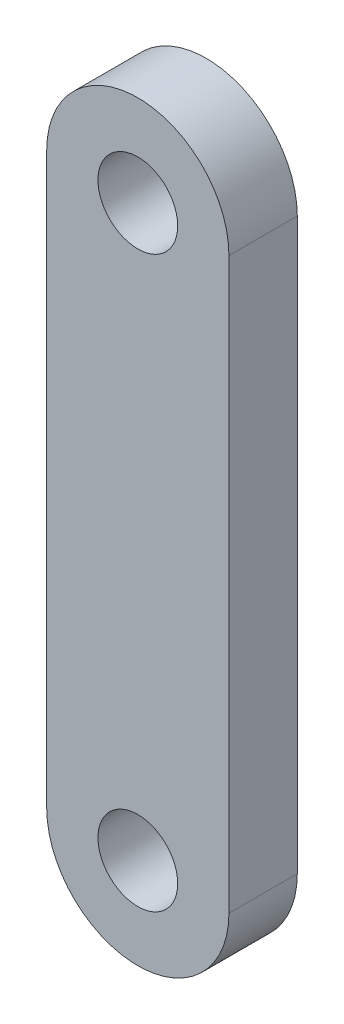
SolidWorks part; units mm, degrees
ref_plane "Plano frontal" through (0, 0, 0) normal (0, 0, 1) x (1, 0, 0)
ref_plane "Plano superior" through (0, 0, 0) normal (0, 1, 0) x (1, 0, 0)
ref_plane "Plano direito" through (0, 0, 0) normal (1, 0, 0) x (0, 0, -1)
sketch "Esboço1" plane through (0, 0, 0) normal (0, 0, 1) x (1, 0, 0)
  line L0 (0, 12.5) -> (0, -12.5) construction
  line L1 (0, 12.5) -> (0, -12.5) construction
  line L2 (4, 12.5) -> (4, -12.5)
  line L3 (-4, 12.5) -> (-4, -12.5)
  arc A0 (4, 12.5) -> (-4, 12.5) centre (0, 12.5) ccw
  arc A1 (-4, -12.5) -> (4, -12.5) centre (0, -12.5) ccw
  circle A2 centre (0, 12.5) radius 1.75
  circle A3 centre (0, -12.5) radius 1.75
  point P0 (0, 0)
  point P4 (0, 0)
  dimension "D2" = 4
  dimension "D3" = 3.5
  dimension "D4" = 3.5
  dimension "D1" = 25
extrude "Ressalto-extrusão1" add sketch "Esboço1" along normal blind 3
